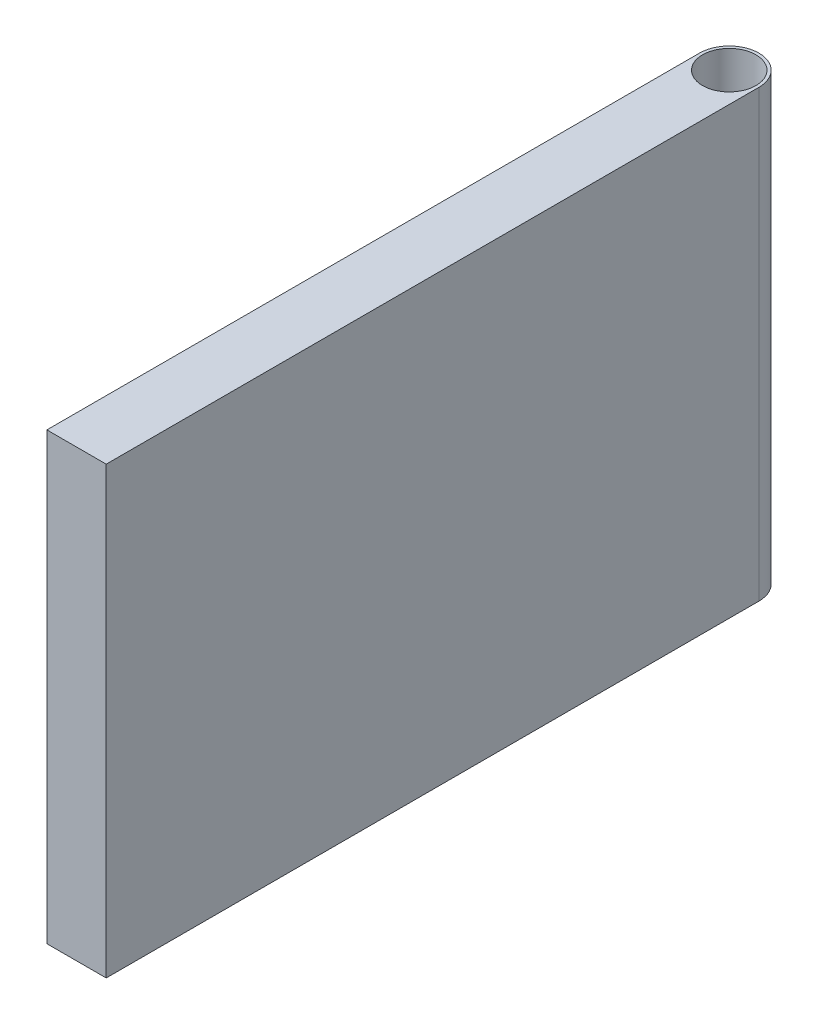
SolidWorks part; units mm, degrees
ref_plane "Front Plane" through (0, 0, 0) normal (0, 0, 1) x (1, 0, 0)
ref_plane "Top Plane" through (0, 0, 0) normal (0, 1, 0) x (1, 0, 0)
ref_plane "Right Plane" through (0, 0, 0) normal (1, 0, 0) x (0, 0, -1)
sketch "Sketch1" plane through (0, 0, 0) normal (1, 0, 0) x (0, 0, -1)
  line L1 (-110, 75) -> (110, 75)
  line L2 (-110, 75) -> (-110, -75)
  line L3 (-110, -75) -> (110, -75)
  line L4 (110, 75) -> (110, -75)
  line L5 (-110, 75) -> (110, -75) construction
  line L6 (-110, -75) -> (110, 75) construction
  point P0 (0, 0)
  dimension "D1" = 150
  dimension "D2" = 220
extrude "Boss-Extrude2" add sketch "Sketch1" along normal blind 20
sketch "Sketch3" plane through (0, 75, 0) normal (0, 1, 0) x (1, 0, 0)
  line L0 (20, 110) -> (0, 110) construction
  circle A0 centre (10, 110) radius 9
  circle A1 centre (10, 110) radius 10
  dimension "D1" = 18
extrude "Boss-Extrude3" add sketch "Sketch3" against normal blind 150
sketch "Sketch4" plane through (0, 75, 0) normal (0, 1, 0) x (1, 0, 0)
  line L0 (19, 110) -> (1, 110) construction
  circle A0 centre (10, 110) radius 9
  dimension "D1" = 18
extrude "Cut-Extrude1" cut sketch "Sketch4" against normal blind 150
